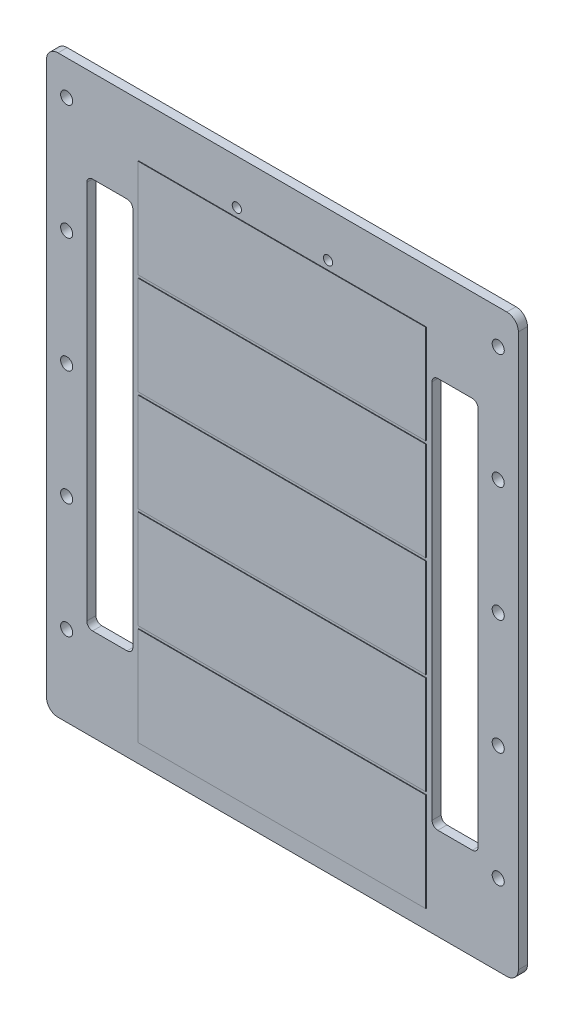
SolidWorks part; units mm, degrees
material "Oshpark board"
ref_plane "Front Plane" through (0, 0, 0) normal (0, 0, 1) x (1, 0, 0)
ref_plane "Top Plane" through (0, 0, 0) normal (0, 1, 0) x (1, 0, 0)
ref_plane "Right Plane" through (0, 0, 0) normal (1, 0, 0) x (0, 0, -1)
ref_plane "Plane4" through (0, 0, 1.5875) normal (0, 0, 1) x (1, 0, 0)
sketch "Sketch1" plane through (0, 0, 1.5875) normal (0, 0, 1) x (1, 0, 0)
  line L0 (41, -50) -> (41, 50)
  line L1 (41, 50) -> (-41, 50)
  line L2 (-41, 50) -> (-41, -50)
  line L3 (-41, -50) -> (41, -50)
  line L4 (-41, 50) -> (41, -50) construction
  point P4 (0, 0)
  dimension "D1" = 100
  dimension "D2" = 82
extrude "board" add sketch "Sketch1" against normal blind 1.5875
sketch "Sketch2" plane through (0, 0, 1.5875) normal (0, 0, 1) x (1, 0, 0)
  line L0 (-26, 34) -> (-34, 34)
  line L1 (-34, 34) -> (-34, -34)
  line L2 (-34, -34) -> (-26, -34)
  line L3 (-26, -34) -> (-26, 34)
  line L4 (0, 50) -> (0, -50) construction
  line L5 (41, 50) -> (-41, 50) construction
  line L6 (-41, -50) -> (41, -50) construction
  line L7 (-34, 34) -> (-26, -34) construction
  line L8 (34, -34) -> (26, -34)
  line L9 (34, 34) -> (34, -34)
  line L10 (26, 34) -> (34, 34)
  line L11 (26, -34) -> (26, 34)
  point P10 (-30, 0)
  dimension "D1" = 68
  dimension "D2" = 8
  dimension "D3" = 30
extrude "access holes" cut sketch "Sketch2" against normal through all
hole_wizard "screw holes" positions "Sketch10" profile "Sketch9" hole size "#1" standard "ANSI Inch"
sketch "Sketch10" plane through (0, 0, 0) normal (0, 0, -1) x (-1, 0, 0)
  line L0 (34, 34) -> (41, 34) construction
  line L1 (41, 50) -> (41, -50) construction
  line L3 (37.5, 44) -> (37.5, 24) construction
  line L6 (0, 50) -> (0, -50) construction
  line L7 (-41, 50) -> (41, 50) construction
  line L8 (41, -50) -> (-41, -50) construction
  point P9 (37.5, 44)
  point P15 (37.5, 24)
  point P16 (37.5, 4)
  point P17 (37.5, -16)
  point P18 (37.5, -36)
  point P33 (37.5, 34)
  point P39 (37.5, 34)
  point P51 (0, 0)
  point P52 (-37.5, -36)
  point P53 (-37.5, -16)
  point P54 (-37.5, 4)
  point P55 (-37.5, 24)
  point P56 (-37.5, 44)
  dimension "D2" = 20
  dimension "D1" = 5
sketch "Sketch9" plane through (-37.5, 44, 0) normal (1, 0, 0) x (0, 1, 0)
  line L0 (0, 0) -> (0, 1.5875)
  line L1 (0, 1.5875) -> (1.05, 1.5875)
  line L2 (1.05, 1.5875) -> (1.05, 0)
  line L5 (1.05, 0) -> (0, 0)
  line L11 (0, -6.35) -> (0, 107.95) construction
  dimension "Thru Hole Dia." = 2.1
  dimension "Thru Hole Depth" = 1.5875
hole_wizard "connector holes" positions "Sketch12" profile "Sketch11" legacy
sketch "Sketch12" plane through (0, 0, 0) normal (0, 0, -1) x (-1, 0, 0)
  line L0 (0, 50) -> (0, -50) construction
  line L1 (-41, 50) -> (41, 50) construction
  line L2 (41, -50) -> (-41, -50) construction
  point P1 (7.925, 42.25)
  point P10 (-7.925, 42.25)
  dimension "D1" = 7.75
  dimension "D2" = 15.85
sketch "Sketch11" plane through (-7.925, 42.25, 0) normal (1, 0, 0) x (0, 1, 0)
  line L0 (0, 0) -> (0, 1.5875)
  line L1 (0, 1.5875) -> (0.8, 1.5875)
  line L2 (0.8, 1.5875) -> (0.8, 0)
  line L3 (0.8, 0) -> (0, 0)
  line L4 (0, 110) -> (0, -10) construction
  dimension "Diameter" = 1.6
  dimension "Depth" = 1.5875
sketch "Sketch4" plane through (0, 0, 1.5875) normal (0, 0, 1) x (1, 0, 0)
  line L0 (25, 23.65) -> (-25, 23.65)
  line L1 (-25, 23.65) -> (-25, 40.75)
  line L2 (-25, 40.75) -> (25, 40.75)
  line L3 (25, 40.75) -> (25, 23.65)
  line L4 (-25, 40.75) -> (25, 23.65) construction
  line L5 (25, 6.05) -> (-25, 6.05)
  line L6 (-25, 6.05) -> (-25, 23.15)
  line L7 (-25, 23.15) -> (25, 23.15)
  line L8 (25, 23.15) -> (25, 6.05)
  line L9 (-25, 23.15) -> (25, 6.05) construction
  line L10 (25, -11.55) -> (-25, -11.55)
  line L11 (-25, -11.55) -> (-25, 5.55)
  line L12 (-25, 5.55) -> (25, 5.55)
  line L13 (25, 5.55) -> (25, -11.55)
  line L14 (-25, 5.55) -> (25, -11.55) construction
  line L15 (25, -29.15) -> (-25, -29.15)
  line L16 (-25, -29.15) -> (-25, -12.05)
  line L17 (-25, -12.05) -> (25, -12.05)
  line L18 (25, -12.05) -> (25, -29.15)
  line L19 (-25, -12.05) -> (25, -29.15) construction
  line L20 (25, -46.75) -> (-25, -46.75)
  line L21 (-25, -46.75) -> (-25, -29.65)
  line L22 (-25, -29.65) -> (25, -29.65)
  line L23 (25, -29.65) -> (25, -46.75)
  line L24 (-25, -29.65) -> (25, -46.75) construction
  line L26 (-7.925, 41.45) -> (-7.925, 40.75) construction
  circle A1 centre (-7.925, 42.25) radius 0.8 construction
  circle A2 centre (-7.925, 42.25) radius 0.8 construction
  point P4 (0, 32.2)
  point P25 (0, 14.6)
  dimension "D6" = 0.5
  dimension "D1" = 50
  dimension "D2" = 17.1
  dimension "D4" = 0.7
  dimension "D3" = 5
extrude "solar cells" add sketch "Sketch4" along normal blind 0.1
sketch "Sketch5" [suppressed] plane through (0, 0, 1.5875) normal (0, 0, 1) x (1, 0, 0)
  line L0 (25, -11.55) -> (-25, -11.55)
  line L1 (-25, -11.55) -> (-25, 5.55)
  line L2 (-25, 5.55) -> (25, 5.55)
  line L3 (25, 5.55) -> (25, -11.55)
extrude "Boss-Extrude3" [suppressed] add sketch "Sketch5" along normal blind 0.1
sketch "Sketch6" [suppressed] plane through (0, 0, 1.5875) normal (0, 0, 1) x (1, 0, 0)
  line L0 (25, -29.15) -> (-25, -29.15)
  line L1 (-25, -29.15) -> (-25, -12.05)
  line L2 (-25, -12.05) -> (25, -12.05)
  line L3 (25, -12.05) -> (25, -29.15)
extrude "Boss-Extrude4" [suppressed] add sketch "Sketch6" along normal blind 0.1
sketch "Sketch7" plane through (0, 0, 1.5875) normal (0, 0, 1) x (1, 0, 0)
  line L0 (25, 6.05) -> (-25, 6.05)
  line L1 (-25, 6.05) -> (-25, 23.15)
  line L2 (-25, 23.15) -> (25, 23.15)
  line L3 (25, 23.15) -> (25, 6.05)
extrude "Boss-Extrude5" [suppressed] add sketch "Sketch7" along normal blind 0.1
sketch "Sketch8" plane through (0, 0, 1.5875) normal (0, 0, 1) x (1, 0, 0)
  line L0 (25, -46.75) -> (-25, -46.75)
  line L1 (-25, -46.75) -> (-25, -29.65)
  line L2 (-25, -29.65) -> (25, -29.65)
  line L3 (25, -29.65) -> (25, -46.75)
extrude "Boss-Extrude6" [suppressed] add sketch "Sketch8" along normal blind 0.1
fillet "outer radius" radius 2 4 edges at (41, -50, 0.7938) (41, 50, 0.7938) (-41, -50, 0.7938) (-41, 50, 0.7938)
fillet "access fillet" radius 1 8 edges at (26, -34, 0.7938) (34, -34, 0.7938) (34, 34, 0.7938) (26, 34, 0.7938) (-34, 34, 0.7938) (-26, 34, 0.7938) (-26, -34, 0.7938) (-34, -34, 0.7938)
